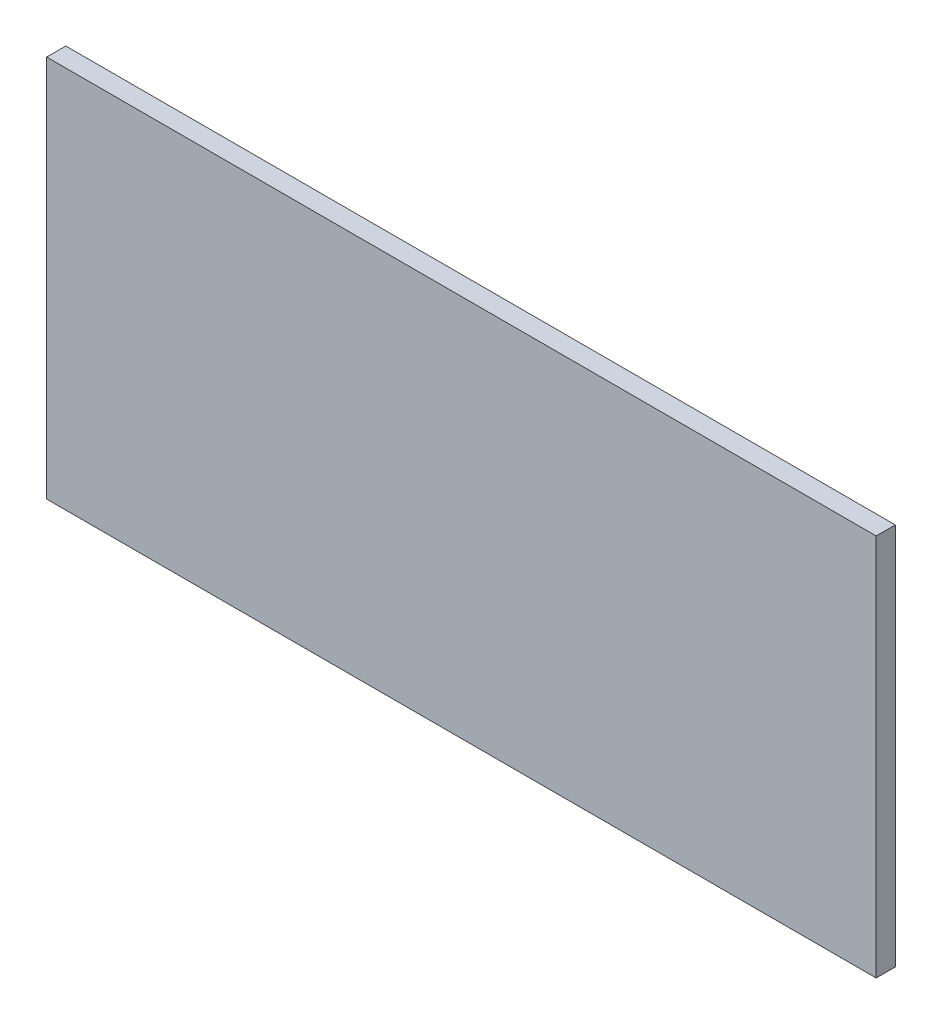
SolidWorks part; units mm, degrees
ref_plane "Front Plane" through (0, 0, 0) normal (0, 0, 1) x (1, 0, 0)
ref_plane "Top Plane" through (0, 0, 0) normal (0, 1, 0) x (1, 0, 0)
ref_plane "Right Plane" through (0, 0, 0) normal (1, 0, 0) x (0, 0, -1)
sketch "Sketch1" plane through (0, 0, 0) normal (0, 0, 1) x (1, 0, 0)
  line L0 (97.82, 27.8614) -> (97.82, 8.8614) construction
  line L1 (72.82, 27.8614) -> (122.82, 27.8614) construction
  line L2 (122.82, 8.8614) -> (72.82, 8.8614) construction
  line L3 (65.32, 33.3614) -> (65.32, 3.3614) construction
  line L5 (130.32, 3.3614) -> (130.32, 33.3614) construction
  line L6 (130.32, 33.3614) -> (65.32, 33.3614) construction
  line L7 (65.32, 33.3614) -> (65.32, 3.3614) construction
  line L8 (130.32, 3.3614) -> (65.32, 33.3614) construction
  line L9 (130.32, 33.3614) -> (65.32, 3.3614) construction
  line L12 (130.32, 33.3614) -> (65.32, 33.3614) construction
  line L13 (65.32, 3.3614) -> (65.32, 33.3614)
  line L14 (65.32, 33.3614) -> (130.32, 33.3614)
  line L15 (130.32, 33.3614) -> (130.32, 3.3614)
  line L16 (130.32, 3.3614) -> (65.32, 3.3614)
  point P6 (97.82, 18.3614)
  dimension "D1" = 65
  dimension "D2" = 30
extrude "Boss-Extrude1" add sketch "Sketch1" against normal blind 1.5
sketch "Sketch2" plane through (0, 0, -1.5) normal (0, 0, -1) x (-1, 0, 0)
  line L0 (-122.82, 25.3614) -> (-72.82, 25.3614) construction
  line L1 (-122.82, 8.8614) -> (-122.82, 27.8614) construction
  line L2 (-72.82, 8.8614) -> (-72.82, 27.8614) construction
  line L3 (-122.82, 11.3614) -> (-72.82, 11.3614) construction
  line L4 (-75.32, 27.8614) -> (-75.32, 8.8614) construction
  line L5 (-72.82, 27.8614) -> (-122.82, 27.8614) construction
  line L6 (-122.82, 8.8614) -> (-72.82, 8.8614) construction
  line L7 (-120.32, 27.8614) -> (-120.32, 8.8614) construction
  line L8 (-120.32, 27.8614) -> (-75.32, 27.8614)
  line L9 (-72.82, 25.3614) -> (-72.82, 11.3614)
  line L10 (-75.32, 8.8614) -> (-120.32, 8.8614)
  line L12 (-122.82, 11.3614) -> (-122.82, 25.3614)
  arc A0 (-122.82, 25.3614) -> (-120.32, 27.8614) centre (-120.32, 25.3614) cw
  arc A1 (-75.32, 27.8614) -> (-72.82, 25.3614) centre (-75.32, 25.3614) cw
  arc A2 (-75.32, 8.8614) -> (-72.82, 11.3614) centre (-75.32, 11.3614) ccw
  arc A3 (-120.32, 8.8614) -> (-122.82, 11.3614) centre (-120.32, 11.3614) cw
  dimension "D1" = 2.5
extrude "Boss-Extrude2" add sketch "Sketch2" along normal blind 1.5 separate body
